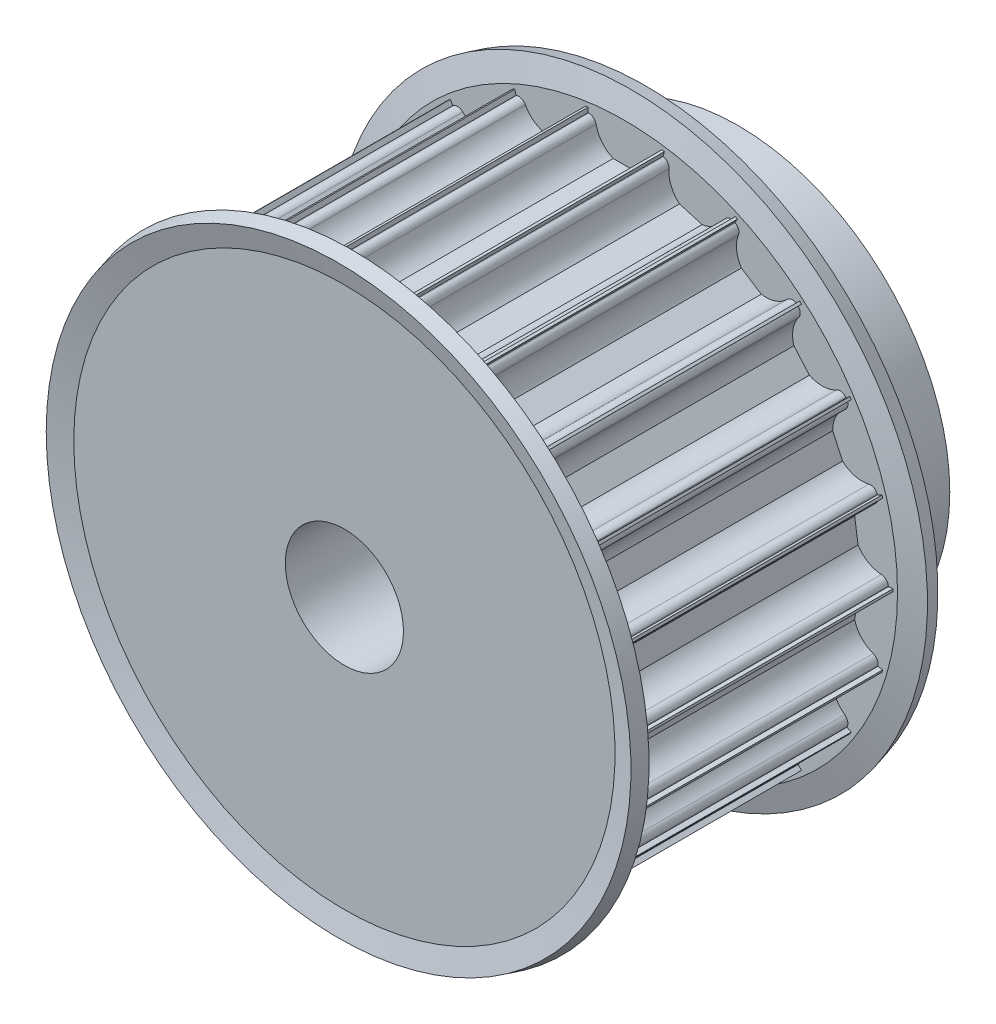
SolidWorks part; units mm, degrees
ref_plane "Front Plane" through (0, 0, 0) normal (0, 0, 1) x (1, 0, 0)
ref_plane "Top Plane" through (0, 0, 0) normal (0, 1, 0) x (1, 0, 0)
ref_plane "Right Plane" through (0, 0, 0) normal (1, 0, 0) x (0, 0, -1)
sketch "Sketch1" plane through (0, 0, 0) normal (1, 0, 0) x (0, 0, -1)
  line L0 (0, 0) -> (45.3408, 0) construction
  line L1 (0, 6) -> (40, 6)
  line L2 (40, 6) -> (40, 21.5)
  line L3 (40, 21.5) -> (30, 21.5)
  line L4 (30, 21.5) -> (30, 27.25)
  line L5 (30, 27.25) -> (0, 27.25)
  line L6 (0, 27.25) -> (0, 6)
  point P5 (45.3408, 0)
  point P10 (0, 0)
  dimension "D1" = 6
  dimension "D2" = 27.25
  dimension "D3" = 30
  dimension "D4" = 10
  dimension "D5" = 15.5
revolve "Revolve1" add sketch "Sketch1" angle 360 about L0
sketch "Sketch2" plane through (0, 0, 0) normal (0, 0, 1) x (1, 0, 0)
  line L0 (-3.6742, 26.5) -> (-3.75, 26.5)
  line L1 (-3.75, 26.5) -> (-3.75, 28.5)
  line L2 (-3.75, 28.5) -> (3.75, 28.5)
  line L3 (3.75, 28.5) -> (3.75, 26.5)
  line L4 (3.75, 26.5) -> (3.6742, 26.5)
  line L5 (-1.199, 23.75) -> (1.199, 23.75)
  arc A0 (2.9394, 25.9) -> (1.199, 23.75) centre (0, 26.5) cw
  arc A1 (2.9394, 25.9) -> (3.6742, 26.5) centre (3.6742, 25.75) cw
  arc A2 (-2.9394, 25.9) -> (-3.6742, 26.5) centre (-3.6742, 25.75) ccw
  arc A3 (-1.199, 23.75) -> (-2.9394, 25.9) centre (0, 26.5) cw
  point P3 (0, 0)
  point P9 (0, 28.5)
  point P12 (3, 26.5)
  point P15 (-3, 26.5)
  dimension "D1" = 3
  dimension "D5" = 0.75
  dimension "D2" = 26.5
  dimension "D3" = 7.5
  dimension "D4" = 2
  dimension "D6" = 2.75
extrude "Cut-Extrude1" cut sketch "Sketch2" against normal up to next
pattern_circular "CirPattern1" count 22 over 360 about axis through (0, 0, 0) along (0, 0, 1) of "Cut-Extrude1"
sketch "Sketch3" plane through (0, 0, 0) normal (1, 0, 0) x (0, 0, -1)
  line L0 (15, 26.9539) -> (15, 6.5954) construction
  line L1 (30, 26.9539) -> (0, 26.9539) construction
  line L2 (30, 6.5954) -> (0, 6.5954) construction
  line L3 (30, 21.5) -> (30, 27.4925)
  line L4 (30, 27.4925) -> (30.592, 29.7018)
  line L5 (30.592, 29.7018) -> (29.1431, 30.09)
  line L6 (29.1431, 30.09) -> (28.5, 27.69)
  line L7 (28.5, 27.69) -> (28.5, 21.5)
  line L8 (28.5, 21.5) -> (30, 21.5)
  line L9 (1.5, 21.5) -> (0, 21.5)
  line L10 (1.5, 27.69) -> (1.5, 21.5)
  line L11 (0.8569, 30.09) -> (1.5, 27.69)
  line L12 (-0.592, 29.7018) -> (0.8569, 30.09)
  line L13 (0, 27.4925) -> (-0.592, 29.7018)
  line L14 (0, 21.5) -> (0, 27.4925)
  dimension "D1" = 15
  dimension "D2" = 6.19
  dimension "D3" = 1.5
  dimension "D4" = 2.4
ref_axis "Axis1" through (0, 0, -28.9943) along (0, 0, 1)
revolve "Revolve2" add sketch "Sketch3" angle 360 about axis through (0, 0, -28.9943) along (0, 0, 1)
